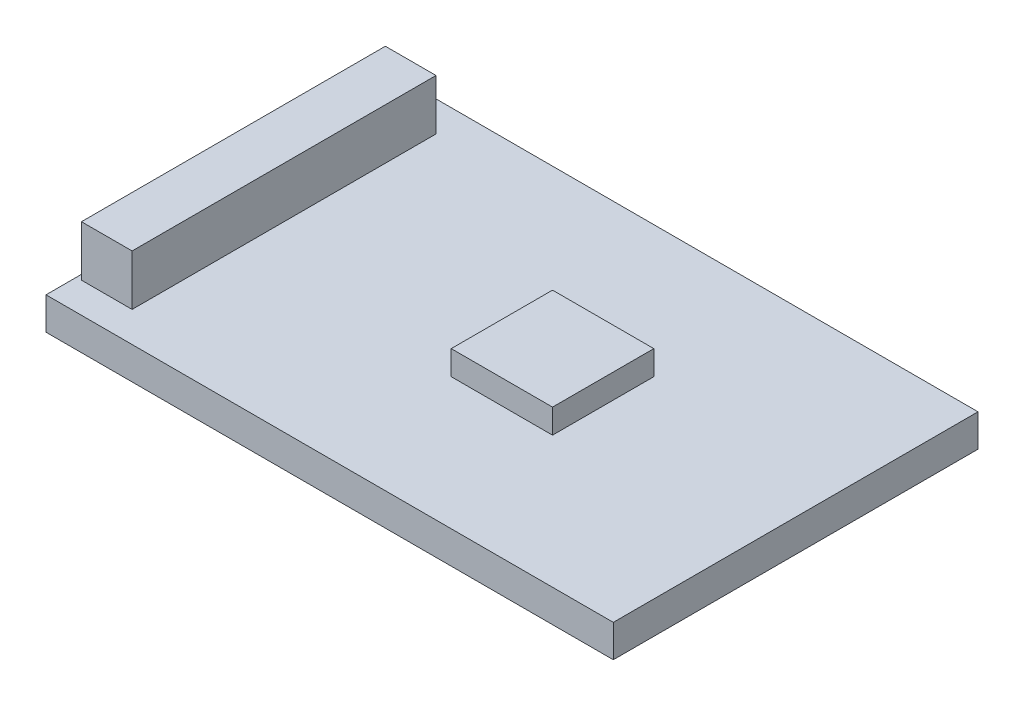
SolidWorks part; units mm, degrees
ref_plane "Front Plane" through (0, 0, 0) normal (0, 0, 1) x (1, 0, 0)
ref_plane "Top Plane" through (0, 0, 0) normal (0, 1, 0) x (1, 0, 0)
ref_plane "Right Plane" through (0, 0, 0) normal (1, 0, 0) x (0, 0, -1)
other "Configuration Table"
sketch "Sketch1" plane through (0, 0, 0) normal (0, 1, 0) x (1, 0, 0)
  line L1 (-14, -9) -> (14, -9)
  line L2 (-14, -9) -> (-14, 9)
  line L3 (-14, 9) -> (14, 9)
  line L4 (14, -9) -> (14, 9)
  line L5 (-14, -9) -> (14, 9) construction
  line L6 (-14, 9) -> (14, -9) construction
extrude "PCB" add sketch "Sketch1" along normal blind 1.6
sketch "Sketch2" plane through (0, 0, 0) normal (0, 1, 0) x (1, 0, 0)
  line L1 (-0.5, -2.5) -> (4.5, -2.5)
  line L2 (-0.5, -2.5) -> (-0.5, 2.5)
  line L3 (-0.5, 2.5) -> (4.5, 2.5)
  line L4 (4.5, -2.5) -> (4.5, 2.5)
  line L5 (-0.5, -2.5) -> (4.5, 2.5) construction
  line L6 (-0.5, 2.5) -> (4.5, -2.5) construction
extrude "ADS1115_Chip" add sketch "Sketch2" along normal blind 1.2 from offset 1.6
sketch "Sketch3" plane through (0, 0, 0) normal (0, 1, 0) x (1, 0, 0)
  line L1 (-13.75, -7.5) -> (-11.25, -7.5)
  line L2 (-13.75, -7.5) -> (-13.75, 7.5)
  line L3 (-13.75, 7.5) -> (-11.25, 7.5)
  line L4 (-11.25, -7.5) -> (-11.25, 7.5)
  line L5 (-13.75, -7.5) -> (-11.25, 7.5) construction
  line L6 (-13.75, 7.5) -> (-11.25, -7.5) construction
extrude "Header" add sketch "Sketch3" along normal blind 2.5 from offset 1.6
equation "\"ads_L\"= 28.0   'ASSUMPTION: ADS1115 board L (PDF fallback)"
equation "\"ads_W\"= 18.0   'ASSUMPTION: ADS1115 board W (PDF fallback)"
equation "\"pcb_t\"= 1.6   'ASSUMPTION: PCB thickness (standard)"
equation "\"D1@PCB\" = \"pcb_t\""
